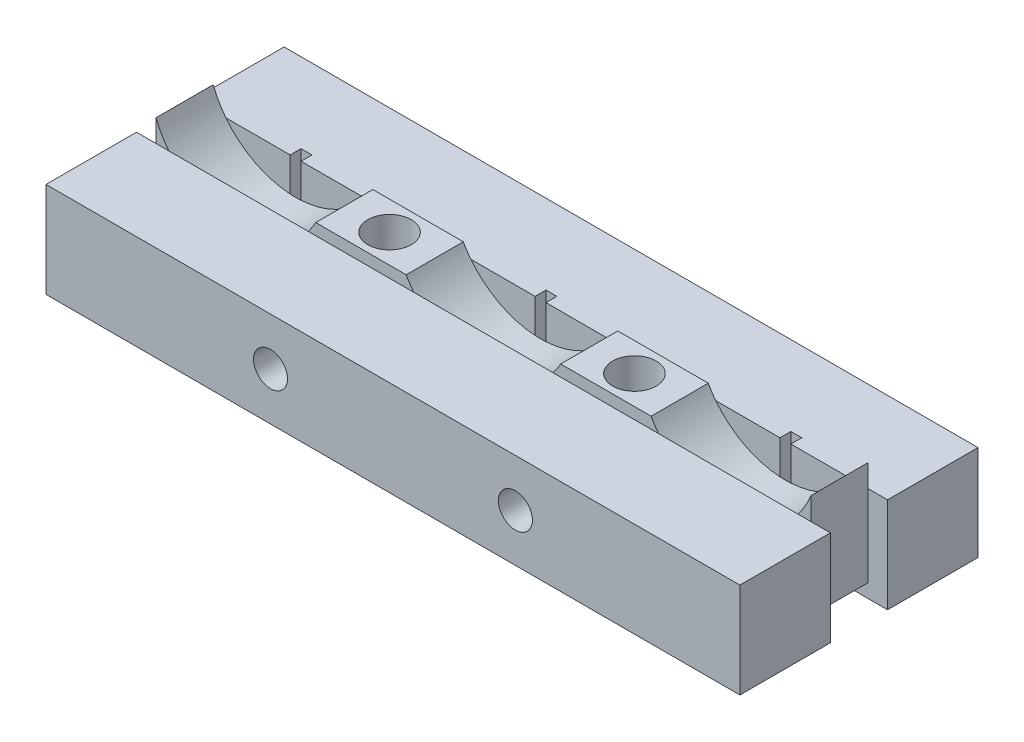
SolidWorks part; units mm, degrees
ref_plane "Front Plane" through (0, 0, 0) normal (0, 0, 1) x (1, 0, 0)
ref_plane "Top Plane" through (0, 0, 0) normal (0, 1, 0) x (1, 0, 0)
ref_plane "Right Plane" through (0, 0, 0) normal (1, 0, 0) x (0, 0, -1)
sketch "Sketch1" plane through (0, 0, 0) normal (0, 0, 1) x (1, 0, 0)
  line L0 (-18.0028, 6) -> (-18.0028, -6) construction
  line L1 (-11.5028, 6) -> (-11.5028, -6) construction
  line L2 (-24.5028, 6) -> (-24.5028, -6) construction
  line L3 (0, 6) -> (0, -6) construction
  line L4 (6.5, 6) -> (6.5, -6) construction
  line L5 (-6.5, 6) -> (-6.5, -6) construction
  line L6 (18.0028, 6) -> (18.0028, -6) construction
  line L7 (24.5028, 6) -> (24.5028, -6) construction
  line L8 (11.5028, 6) -> (11.5028, -6) construction
  line L13 (-18.0028, 6.35) -> (-18.0028, -6.35) construction
  line L18 (-12.3249, -9.1641) -> (-5.6779, -9.1641)
  line L19 (5.6779, -9.1641) -> (12.3249, -9.1641)
  line L20 (-15.9528, 6.35) -> (-15.9528, -6.35) construction
  line L21 (-20.0528, 6.35) -> (-20.0528, -6.35) construction
  line L22 (-0.0028, 6.35) -> (-0.0028, -6.35) construction
  line L23 (2.0472, 6.35) -> (2.0472, -6.35) construction
  line L24 (-2.0528, 6.35) -> (-2.0528, -6.35) construction
  line L25 (17.9972, 6.35) -> (17.9972, -6.35) construction
  line L26 (20.0472, 6.35) -> (20.0472, -6.35) construction
  line L27 (15.9472, 6.35) -> (15.9472, -6.35) construction
  line L28 (24.0606, -8.3563) -> (24.0606, -17)
  line L29 (-24.0606, -8.3563) -> (-24.0606, -17)
  line L30 (-24.0606, -17) -> (24.0606, -17)
  arc A0 (-11.5028, 6) -> (-24.5028, 6) centre (-18.0028, 6) ccw construction
  arc A1 (-24.5028, -6) -> (-11.5028, -6) centre (-18.0028, -6) ccw construction
  arc A2 (6.5, 6) -> (-6.5, 6) centre (0, 6) ccw construction
  arc A3 (-6.5, -6) -> (6.5, -6) centre (0, -6) ccw construction
  arc A4 (24.5028, 6) -> (11.5028, 6) centre (18.0028, 6) ccw construction
  arc A5 (11.5028, -6) -> (24.5028, -6) centre (18.0028, -6) ccw construction
  arc A8 (-15.9528, 6.35) -> (-20.0528, 6.35) centre (-18.0028, 6.35) ccw construction
  arc A9 (-20.0528, -6.35) -> (-15.9528, -6.35) centre (-18.0028, -6.35) ccw construction
  arc A10 (2.0472, 6.35) -> (-2.0528, 6.35) centre (-0.0028, 6.35) ccw construction
  arc A11 (-2.0528, -6.35) -> (2.0472, -6.35) centre (-0.0028, -6.35) ccw construction
  arc A12 (20.0472, 6.35) -> (15.9472, 6.35) centre (17.9972, 6.35) ccw construction
  arc A13 (15.9472, -6.35) -> (20.0472, -6.35) centre (17.9972, -6.35) ccw construction
  arc A14 (-24.0606, -8.3563) -> (-12.3249, -9.1641) centre (-18.0028, -6) ccw
  arc A15 (-5.6779, -9.1641) -> (5.6779, -9.1641) centre (0, -6) ccw
  arc A16 (12.3249, -9.1641) -> (24.0606, -8.3563) centre (18.0028, -6) ccw
  point P3 (-18.0028, 0)
  point P11 (0, 0)
  point P18 (18.0028, 0)
  point P24 (0, 0)
  point P38 (-18.0028, 0)
  point P47 (-0.0028, 0)
  point P54 (17.9972, 0)
  dimension "D3" = 3
  dimension "D1" = 13
  dimension "D2" = 12
  dimension "D4" = 17
  dimension "D5" = 18.0028
  dimension "D11" = 4.1
  dimension "D12" = 12.7
  dimension "D13" = 3
extrude "Boss-Extrude1" add sketch "Sketch1" along normal blind 4.2
sketch "Sketch3" plane through (0, -9.1641, 0) normal (0, 1, 0) x (1, 0, 0)
  line L0 (-12.3249, -2.1) -> (-5.6779, -2.1) construction
  line L1 (-12.3249, -4.2) -> (-12.3249, 0) construction
  line L2 (-5.6779, -4.2) -> (-5.6779, 0) construction
  circle A0 centre (-9.0014, -2.1) radius 1.6
  dimension "D1" = 3.2
extrude "Cut-Extrude3" cut sketch "Sketch3" against normal through all
pattern_linear "LPattern1" count 2 spacing 18 along (1, 0, 0) of "Cut-Extrude3"
ref_plane "Plane2" through (0, 0, 2.1) normal (0, 0, 1) x (1, 0, 0)
sketch "Sketch6" plane through (0, 0, 0) normal (0, 0, -1) x (-1, 0, 0)
  line L0 (24.0606, -17) -> (-24.0606, -17) construction
  line L1 (-25.5, -17) -> (25.5, -17)
  line L2 (-25.5, -17) -> (-25.5, -10)
  line L3 (-25.5, -10) -> (25.5, -10)
  line L4 (25.5, -17) -> (25.5, -10)
  point P4 (0, -17)
  point P7 (0, -17)
  dimension "D1" = 7
  dimension "D2" = 51
extrude "Boss-Extrude3" add sketch "Sketch6" along normal blind 6.65
sketch "Sketch7" plane through (0, -17, 0) normal (0, -1, 0) x (1, 0, 0)
  line L0 (-18.0028, 0) -> (-18.0028, 4.2) construction
  line L1 (-15.9528, 0) -> (-20.0528, 0) construction
  line L2 (-24.0606, 4.2) -> (24.0606, 4.2) construction
  line L3 (0.3972, 3.4) -> (0.3972, 4.2)
  line L4 (-18.4028, -0.8) -> (-17.6028, -0.8)
  line L5 (-18.4028, -0.8) -> (-18.4028, 0)
  line L6 (-18.4028, 0) -> (-17.6028, 0)
  line L7 (-17.6028, -0.8) -> (-17.6028, 0)
  line L8 (-18.4028, -0.8) -> (-17.6028, 0) construction
  line L9 (-18.4028, 0) -> (-17.6028, -0.8) construction
  line L10 (-17.6028, 3.4) -> (-18.4028, 3.4)
  line L11 (-17.6028, 3.4) -> (-17.6028, 4.2)
  line L12 (-17.6028, 4.2) -> (-18.4028, 4.2)
  line L13 (-18.4028, 3.4) -> (-18.4028, 4.2)
  line L14 (-17.6028, 3.4) -> (-18.4028, 4.2) construction
  line L15 (-17.6028, 4.2) -> (-18.4028, 3.4) construction
  line L16 (0.3972, 3.4) -> (-0.4028, 3.4)
  line L17 (-0.4028, 3.4) -> (-0.4028, 4.2)
  line L18 (0.3972, 4.2) -> (-0.4028, 4.2)
  line L19 (-0.4028, -0.8) -> (-0.4028, 0)
  line L20 (-0.4028, -0.8) -> (0.3972, -0.8)
  line L21 (0.3972, -0.8) -> (0.3972, 0)
  line L22 (-0.4028, 0) -> (0.3972, 0)
  line L23 (18.3972, 3.4) -> (18.3972, 4.2)
  line L24 (18.3972, 3.4) -> (17.5972, 3.4)
  line L25 (17.5972, 3.4) -> (17.5972, 4.2)
  line L26 (18.3972, 4.2) -> (17.5972, 4.2)
  line L27 (17.5972, -0.8) -> (17.5972, 0)
  line L28 (17.5972, -0.8) -> (18.3972, -0.8)
  line L29 (18.3972, -0.8) -> (18.3972, 0)
  line L30 (17.5972, 0) -> (18.3972, 0)
  point P6 (-18.0028, -0.4)
  point P11 (-18.0028, 3.8)
  dimension "D1" = 0.8
  dimension "D2" = 0.8
  dimension "D3" = 3
extrude "Cut-Extrude7" cut sketch "Sketch7" against normal through all
sketch "Sketch8" plane through (0, 0, 4.2) normal (0, 0, 1) x (1, 0, 0)
  line L1 (-25.5, -17) -> (25.5, -17)
  line L2 (-25.5, -17) -> (-25.5, -10)
  line L3 (-25.5, -10) -> (25.5, -10)
  line L4 (25.5, -17) -> (25.5, -10)
extrude "Boss-Extrude4" add sketch "Sketch8" along normal blind 6.65
hole_wizard "Tap Drill for M3 Tap1" positions "Sketch12" profile "Sketch13" hole size "M3" standard "DIN"
sketch "Sketch12" plane through (0, 0, -6.65) normal (0, 0, -1) x (-1, 0, 0)
  line L0 (-25.5, -10) -> (-25.5, -17) construction
  line L1 (25.5, -17) -> (25.5, -10) construction
  point P0 (-9, -13.5)
  point P2 (9, -13.5)
  point P11 (-25.5, -13.5)
  dimension "D1" = 16.5
  dimension "D2" = 16.5
sketch "Sketch13" plane through (9, -13.5, -6.65) normal (1, 0, 0) x (0, 1, 0)
  line L0 (0, 0) -> (0, 6.7511)
  line L1 (0, 6.7511) -> (1.25, 6)
  line L2 (1.25, 6) -> (1.25, 0)
  line L5 (1.25, 0) -> (0, 0)
  line L10 (0, 6.7511) -> (-1.25, 6) construction
  line L11 (0, -6.35) -> (0, 107.95) construction
  dimension "Hole Dia." = 2.5
  dimension "Hole Depth" = 6
  dimension "Drill Angle" = 118
ref_plane "Plane3" through (0, 0, 2.1) normal (0, 0, 1) x (1, 0, 0)
ref_plane "Plane4" through (0, 0, 0) normal (-1, 0, 0) x (0, 0, 1)
mirror "Mirror2" about plane through (0, 0, 2.1) normal (0, 0, 1) of "Tap Drill for M3 Tap1"
hole_wizard "M3 Tapped Hole3" positions "3DSketch2" profile "Sketch15" tap size "M3" standard "DIN"
sketch3d "3DSketch2"
  line L0 (-25.5, -17, 10.85) -> (25.5, -17, 10.85) construction
  point P0 (-18, -17, 7.85)
  dimension "D1" = 7.5
  dimension "D2" = 3
sketch "Sketch15" plane through (-18, -17, 7.85) normal (1, 0, 0) x (0, 0, -1)
  line L0 (0, 0) -> (0, 6.2511)
  line L1 (0, 6.2511) -> (1.25, 5.5)
  line L2 (1.25, 5.5) -> (1.25, 0)
  line L5 (1.25, 0) -> (0, 0)
  line L10 (0, 6.2511) -> (-1.25, 5.5) construction
  line L11 (0, -6.35) -> (0, 107.95) construction
  dimension "Tap Drill Dia." = 2.5
  dimension "Tap Drill Depth" = 5.5
  dimension "Drill Angle" = 118
cosmetic thread "Hole Thread5" parameters "D1"=5.5, "D2"=3
pattern_linear "LPattern2" count 2 spacing 36 along (1, 0, 0) count 2 spacing 11.5 along (0, 0, -1) of "M3 Tapped Hole3"
sketch "Sketch16" plane through (0, -17, 0) normal (0, -1, 0) x (1, 0, 0)
  line L1 (-24.0606, 4.2) -> (24.0606, 4.2)
  line L2 (-24.0606, 4.2) -> (-24.0606, 0)
  line L3 (-24.0606, 0) -> (24.0606, 0)
  line L4 (24.0606, 4.2) -> (24.0606, 0)
extrude "Cut-Extrude8" cut sketch "Sketch16" against normal blind 1
